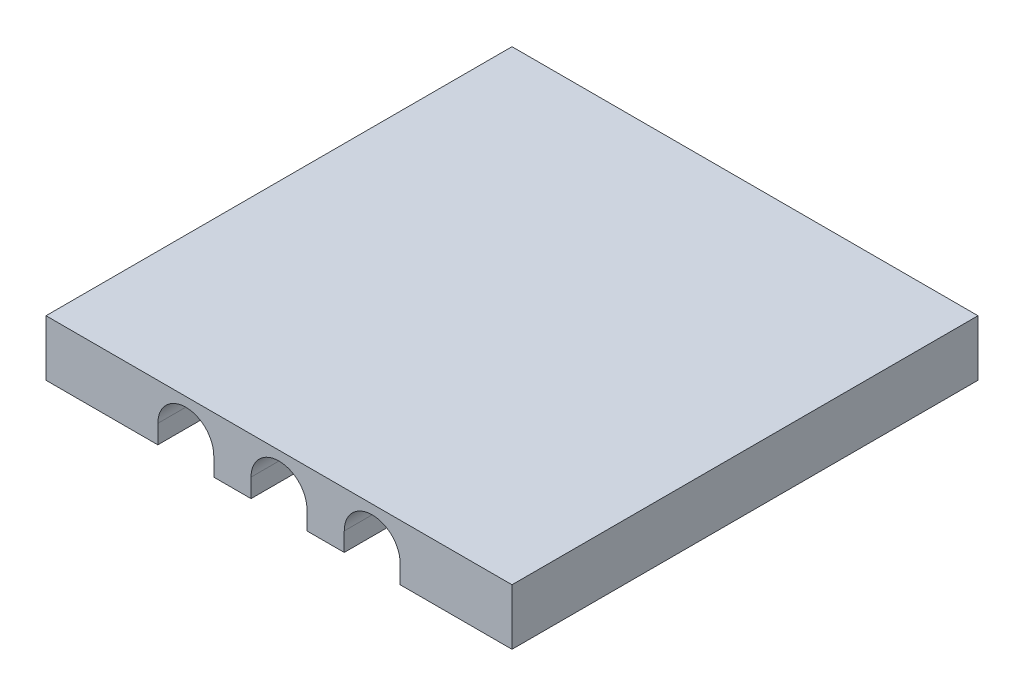
SolidWorks part; units mm, degrees
material "1060 合金"
ref_plane "前视基准面" through (0, 0, 0) normal (0, 0, 1) x (1, 0, 0)
ref_plane "上视基准面" through (0, 0, 0) normal (0, 1, 0) x (1, 0, 0)
ref_plane "右视基准面" through (0, 0, 0) normal (1, 0, 0) x (0, 0, -1)
sketch "草图1" plane through (0, 0, 0) normal (0, 0, 1) x (1, 0, 0)
  line L1 (-25, 3) -> (25, 3)
  line L2 (-25, 3) -> (-25, -3)
  line L3 (-25, -3) -> (25, -3)
  line L4 (25, 3) -> (25, -3)
  line L5 (-25, 3) -> (25, -3) construction
  line L6 (-25, -3) -> (25, 3) construction
  point P0 (0, 0)
  dimension "D1" = 50
  dimension "D2" = 6
extrude "凸台-拉伸1" add sketch "草图1" along normal mid plane 50
sketch "草图2" plane through (0, 0, 25) normal (0, 0, 1) x (1, 0, 0)
  line L0 (25, 3) -> (-25, 3) construction
  line L1 (-3, -1) -> (-3, -3)
  line L2 (-25, -3) -> (25, -3) construction
  line L3 (3, -1) -> (3, -3)
  line L4 (-3, -3) -> (3, -3)
  arc A0 (3, -1) -> (-3, -1) centre (0, -1) ccw
  dimension "D1" = 6
  dimension "D2" = 1
extrude "切除-拉伸1" cut sketch "草图2" against normal up to next
pattern_linear "阵列(线性)1" count 2 spacing 10 along (-1, 0, 0) count 2 spacing 10 along (1, 0, 0) of "切除-拉伸1"
